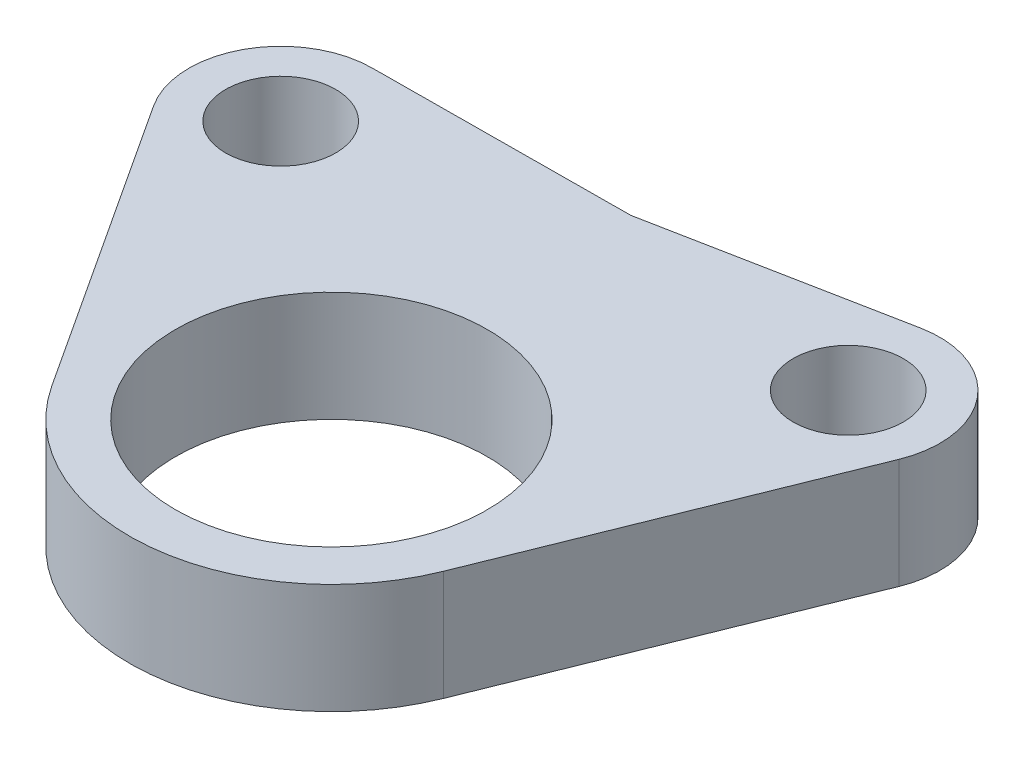
SolidWorks part; units mm, degrees
ref_plane "Alzado" through (0, 0, 0) normal (0, 0, 1) x (1, 0, 0)
ref_plane "Planta" through (0, 0, 0) normal (0, 1, 0) x (1, 0, 0)
ref_plane "Vista lateral" through (0, 0, 0) normal (1, 0, 0) x (0, 0, -1)
sketch "Croquis1" plane through (0, 0, 0) normal (0, 1, 0) x (1, 0, 0)
  line L0 (-9.2101, -6.0145) -> (-19.6418, 9.9599)
  line L1 (-15.4892, 17.6936) -> (-1.4719, 17.7883)
  line L2 (-1.4719, 17.7883) -> (11.7371, 20.363)
  line L3 (17.3316, 13.5873) -> (10.2034, -4.1098)
  line L4 (0, 0) -> (-15.4554, 12.6937) construction
  line L5 (12.6937, 15.4554) -> (0, 0) construction
  arc A0 (-9.2101, -6.0145) -> (10.2034, -4.1098) centre (0, 0) ccw
  circle A1 centre (0, 0) radius 8.5
  arc A2 (-15.4892, 17.6936) -> (-19.6418, 9.9599) centre (-15.4554, 12.6937) ccw
  arc A3 (17.3316, 13.5873) -> (11.7371, 20.363) centre (12.6937, 15.4554) ccw
  circle A4 centre (-15.4554, 12.6937) radius 3
  circle A5 centre (12.6937, 15.4554) radius 3
  point P12 (-24.6518, 17.6317)
  point P15 (20.77, 22.1238)
  dimension "D1" = 17
  dimension "D2" = 22
  dimension "D8" = 5
  dimension "D9" = 5
  dimension "D10" = 6
  dimension "D11" = 6
  dimension "D3" = 20
  dimension "D4" = 20
  dimension "D5" = 90
extrude "Saliente-Extruir1" add sketch "Croquis1" along normal blind 6
